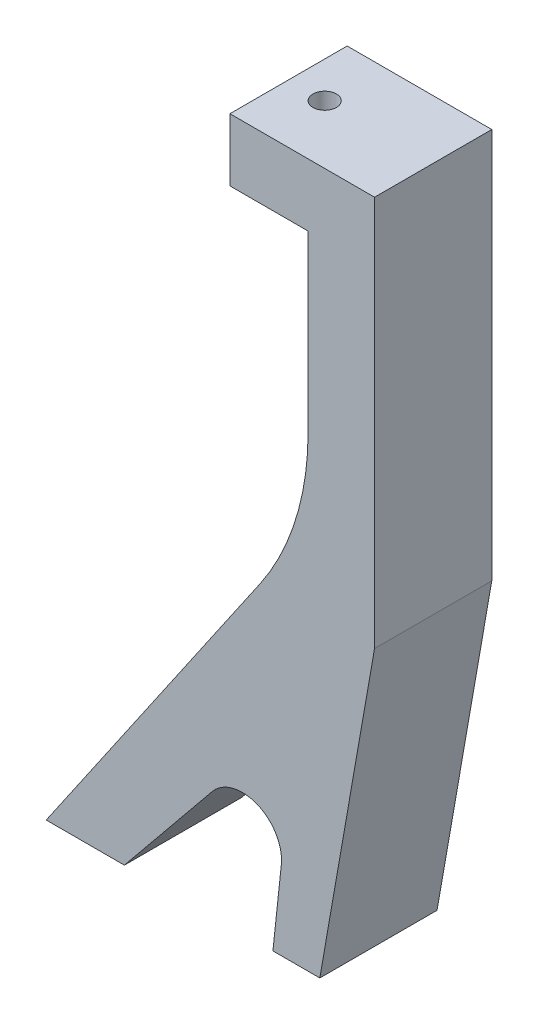
SolidWorks part; units mm, degrees
ref_plane "Front Plane" through (0, 0, 0) normal (0, 0, 1) x (1, 0, 0)
ref_plane "Top Plane" through (0, 0, 0) normal (0, 1, 0) x (1, 0, 0)
ref_plane "Right Plane" through (0, 0, 0) normal (1, 0, 0) x (0, 0, -1)
sketch "Sketch1" plane through (0, 0, 0) normal (0, 0, 1) x (1, 0, 0)
  line L0 (0, 355.2663) -> (0, 0) construction
  line L1 (-6.5, 42) -> (-6.5, 19.6636)
  line L2 (0, 0) -> (-2, 0) construction
  line L4 (-11, 42) -> (-6.5, 42)
  line L5 (2, 0) -> (2, 30)
  line L6 (-6.5, 42) -> (-16.5, 42)
  line L7 (-16.5, 42) -> (-16.5, 50)
  line L8 (-16.5, 50) -> (-11, 50)
  line L11 (-40, -40) -> (-12.6433, -0.1427)
  line L12 (-22.9775, -25) -> (-18.9775, -25)
  line L18 (2, 30) -> (2, 50)
  line L19 (2, 50) -> (-11, 50)
  line L23 (0, 0) -> (0, -40) construction
  line L24 (0, -40) -> (-40, -40) construction
  line L25 (-40, -40) -> (-30, -40)
  line L26 (-30, -40) -> (-18.7725, -26.2331)
  line L27 (-9.9259, -29.9231) -> (-11, -40)
  line L28 (-11, -40) -> (-5, -40)
  line L29 (-5, -40) -> (2, 0)
  arc A0 (-18.7725, -26.2331) -> (-9.9259, -29.9231) centre (-14.8977, -29.3931) cw
  arc A1 (-6.5, 19.6636) -> (-12.6433, -0.1427) centre (-41.5, 19.6636) cw
  point P0 (0, 0)
  dimension "D1" = 5
  dimension "D2" = 35
extrude "Boss-Extrude1" add sketch "Sketch1" along normal blind 15
sketch "Sketch2" plane through (0, 50, 0) normal (0, 1, 0) x (1, 0, 0)
  line L0 (-16.5, -15) -> (-7.25, 0) construction
  line L1 (2, 0) -> (-16.5, 0) construction
  circle A0 centre (-11.875, -7.5) radius 1.5
extrude "Cut-Extrude1" cut sketch "Sketch2" against normal blind 15
